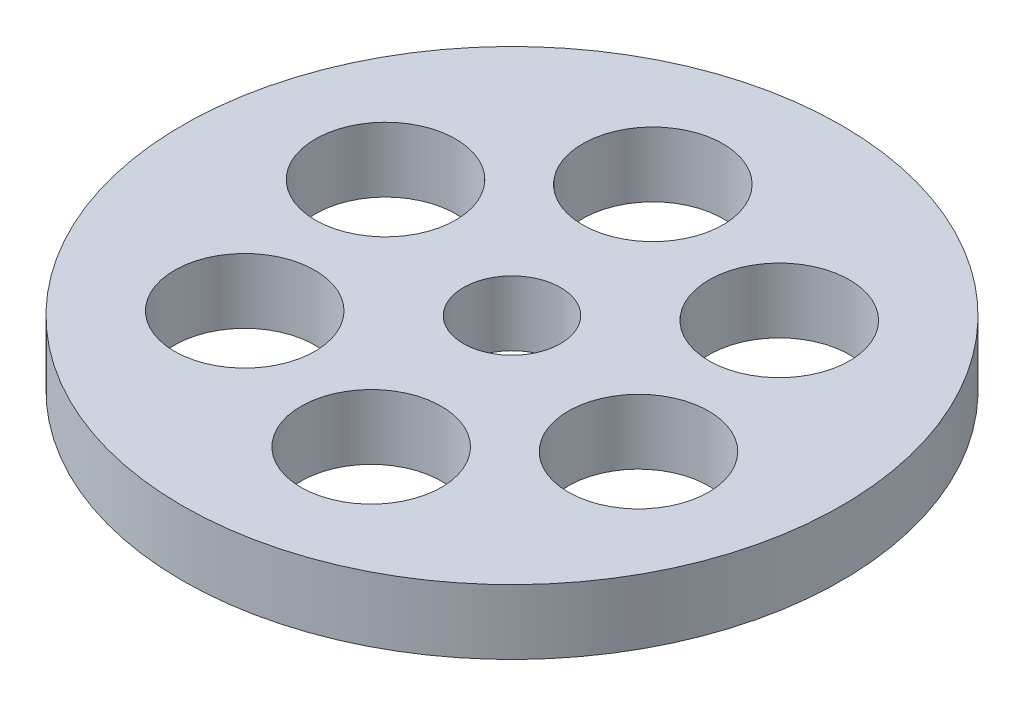
SolidWorks part; units mm, degrees
ref_plane "Płaszczyzna przednia" through (0, 0, 0) normal (0, 0, 1) x (1, 0, 0)
ref_plane "Płaszczyzna górna" through (0, 0, 0) normal (0, 1, 0) x (1, 0, 0)
ref_plane "Płaszczyzna prawa" through (0, 0, 0) normal (1, 0, 0) x (0, 0, -1)
sketch "Szkic2" plane through (0, 0, 0) normal (0, 1, 0) x (1, 0, 0)
  circle A0 centre (0, 0) radius 30.5
  dimension "D1" = 61
extrude "Dodanie-wyciągnięcie2" add sketch "Szkic2" along normal blind 6 contours A0
hole_wizard "Otwór Ø9.0 (9)1" positions "Szkic7" profile "Szkic6" hole size "Ø9.0" standard "Ansi Metric" end condition through all
sketch "Szkic7" plane through (0, 6, 0) normal (0, 1, 0) x (1, 0, 0)
  point P0 (0, 0)
sketch "Szkic6" plane through (0, 6, 0) normal (1, 0, 0) x (0, 0, 1)
  line L0 (0, 0) -> (0, 6)
  line L1 (0, 6) -> (4.5, 6)
  line L2 (4.5, 6) -> (4.5, 0)
  line L5 (4.5, 0) -> (0, 0)
  line L11 (0, -6.35) -> (0, 107.95) construction
  dimension "Średnica otworu na wylot" = 9
  dimension "Głębokość otworu na wylot" = 6
sketch "Szkic8" plane through (0, 6, 0) normal (0, 1, 0) x (1, 0, 0)
  circle A0 centre (-12.7512, -11.9857) radius 6.5
  circle A2 centre (-16.7555, 5.0501) radius 6.5
  circle A3 centre (-4.0043, 17.0357) radius 6.5
  circle A4 centre (12.7512, 11.9857) radius 6.5
  circle A5 centre (16.7555, -5.0501) radius 6.5
  circle A6 centre (4.0043, -17.0357) radius 6.5
  point P16 (0, 0)
  dimension "D1" = 13
  dimension "D2" = 17.5
  dimension "D3" = 6
extrude "Wytnij-wyciągnięcie2" cut sketch "Szkic8" against normal blind 6
